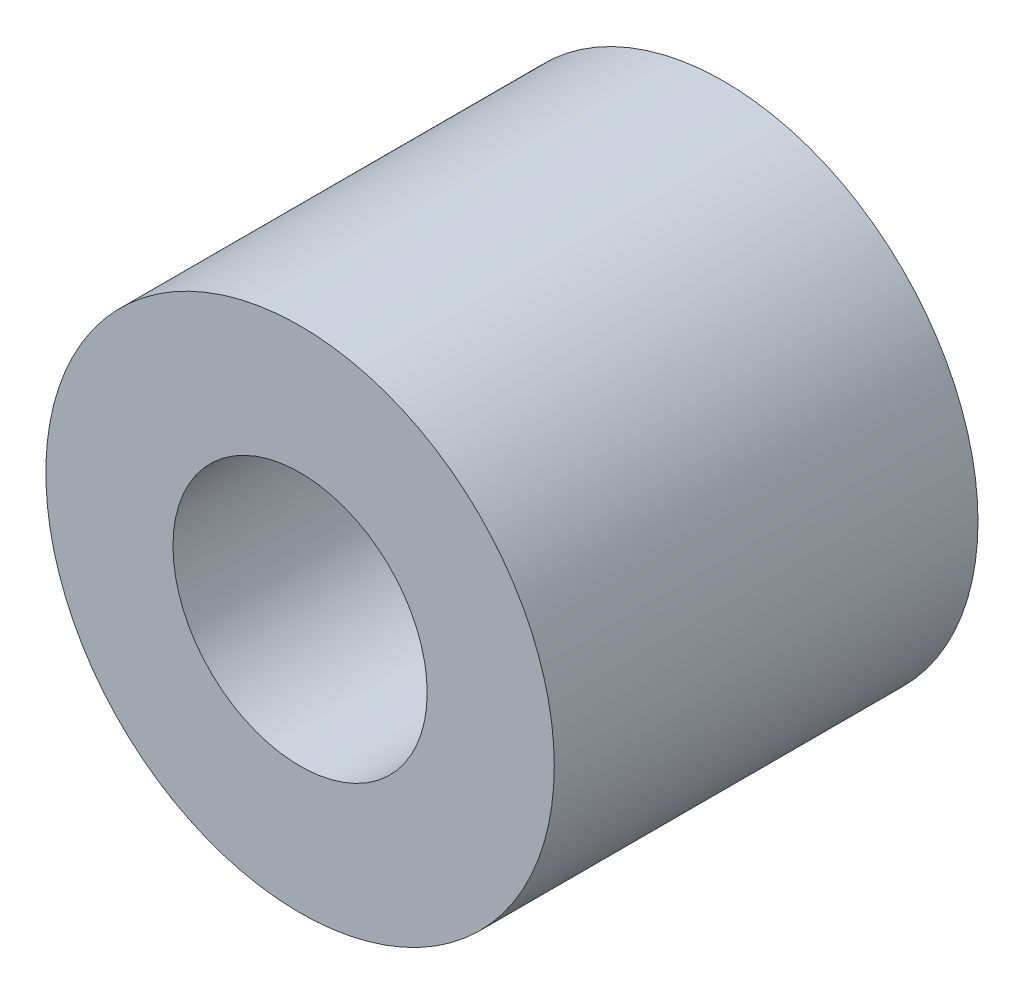
SolidWorks part; units mm, degrees
ref_plane "Plan de face" through (0, 0, 0) normal (0, 0, 1) x (1, 0, 0)
ref_plane "Plan de dessus" through (0, 0, 0) normal (0, 1, 0) x (1, 0, 0)
ref_plane "Plan de droite" through (0, 0, 0) normal (1, 0, 0) x (0, 0, -1)
sketch "Esquisse1" plane through (0, 0, 0) normal (0, 0, 1) x (1, 0, 0)
  circle A0 centre (0, 0) radius 3
  circle A1 centre (0, 0) radius 1.5
  dimension "D1" = 3
  dimension "D2" = 6
extrude "Boss.-Extru.1" add sketch "Esquisse1" along normal blind 5
